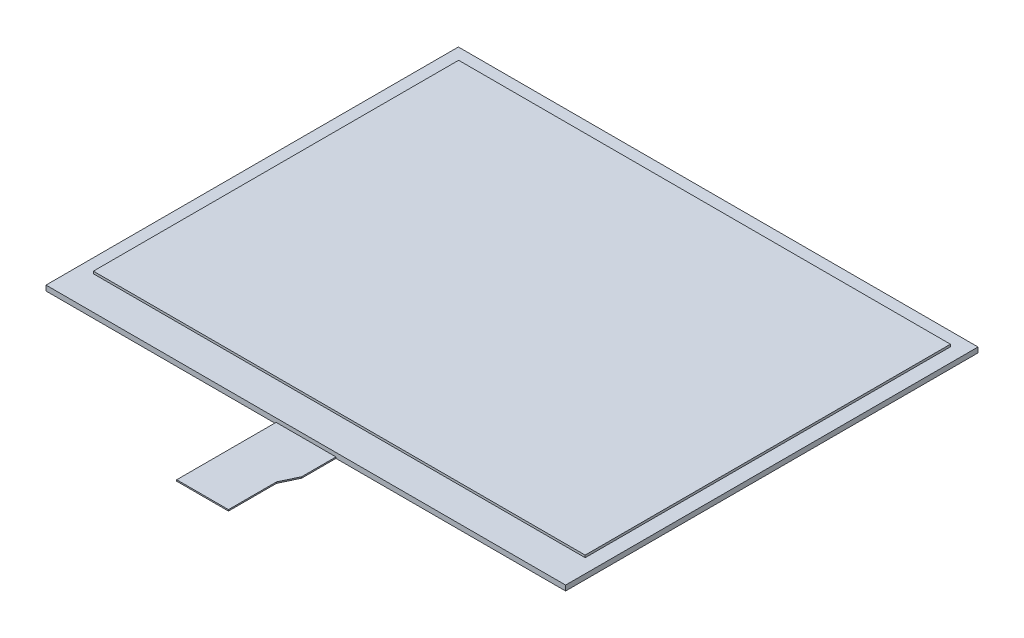
SolidWorks part; units mm, degrees
ref_plane "Front Plane" through (0, 0, 0) normal (0, 0, 1) x (1, 0, 0)
ref_plane "Top Plane" through (0, 0, 0) normal (0, 1, 0) x (1, 0, 0)
ref_plane "Right Plane" through (0, 0, 0) normal (1, 0, 0) x (0, 0, -1)
sketch "Sketch1" plane through (0, 0, 0) normal (0, 1, 0) x (1, 0, 0)
  line L1 (0, 0) -> (125.5, 0)
  line L2 (0, 0) -> (0, -99.6)
  line L3 (0, -99.6) -> (125.5, -99.6)
  line L4 (125.5, 0) -> (125.5, -99.6)
  line L5 (0, 0) -> (125.5, -99.6) construction
  line L6 (0, -99.6) -> (125.5, 0) construction
  point P4 (62.75, -49.8)
  dimension "D1" = 99.6
  dimension "D2" = 125.5
extrude "Boss-Extrude1" add sketch "Sketch1" along normal blind 1.25
sketch "Sketch2" plane through (0, 1.25, 0) normal (0, 1, 0) x (1, 0, 0)
  line L0 (125.5, 0) -> (0, 0) construction
  line L1 (3.36, -3.3) -> (122.14, -3.3)
  line L2 (3.36, -3.3) -> (3.36, -91.52)
  line L3 (3.36, -91.52) -> (122.14, -91.52)
  line L4 (122.14, -3.3) -> (122.14, -91.52)
  line L5 (3.36, -3.3) -> (122.14, -91.52) construction
  line L6 (3.36, -91.52) -> (122.14, -3.3) construction
  line L9 (3.36, -4.8885) -> (0, -4.8885) construction
  line L10 (0, 0) -> (0, -99.6) construction
  line L11 (122.14, -7.4893) -> (125.5, -7.4893) construction
  line L12 (125.5, -99.6) -> (125.5, 0) construction
  point P4 (62.75, -47.41)
  dimension "D1" = 3.3
  dimension "D2" = 118.78
  dimension "D3" = 88.22
extrude "Boss-Extrude2" add sketch "Sketch2" along normal blind 0.55
sketch "Sketch3" plane through (0, 0, 0) normal (0, -1, 0) x (1, 0, 0)
  line L5 (0, 99.6) -> (125.5, 99.6) construction
  line L6 (55.57, 99.6) -> (70.03, 99.6)
  line L10 (55.57, 99.6) -> (55.57, 123.6)
  line L11 (55.57, 123.6) -> (68.07, 123.6)
  line L12 (70.03, 99.6) -> (70.03, 107.8705)
  line L13 (125.5, 99.6) -> (125.5, 0) construction
  line L15 (68.07, 123.6) -> (68.07, 112.0113)
  line L16 (68.07, 112.0113) -> (70.03, 107.8705)
  point P2 (0, 0)
  point P11 (68.07, 112.0113)
  dimension "D1" = 55.47
  dimension "D2" = 57.43
  dimension "D3" = 12.5
  dimension "D4" = 24
extrude "Boss-Extrude3" add sketch "Sketch3" against normal blind 0.315
ref_plane "Plane1" through (62.75, 0, 0) normal (-1, 0, 0) x (0, 0, 1)
